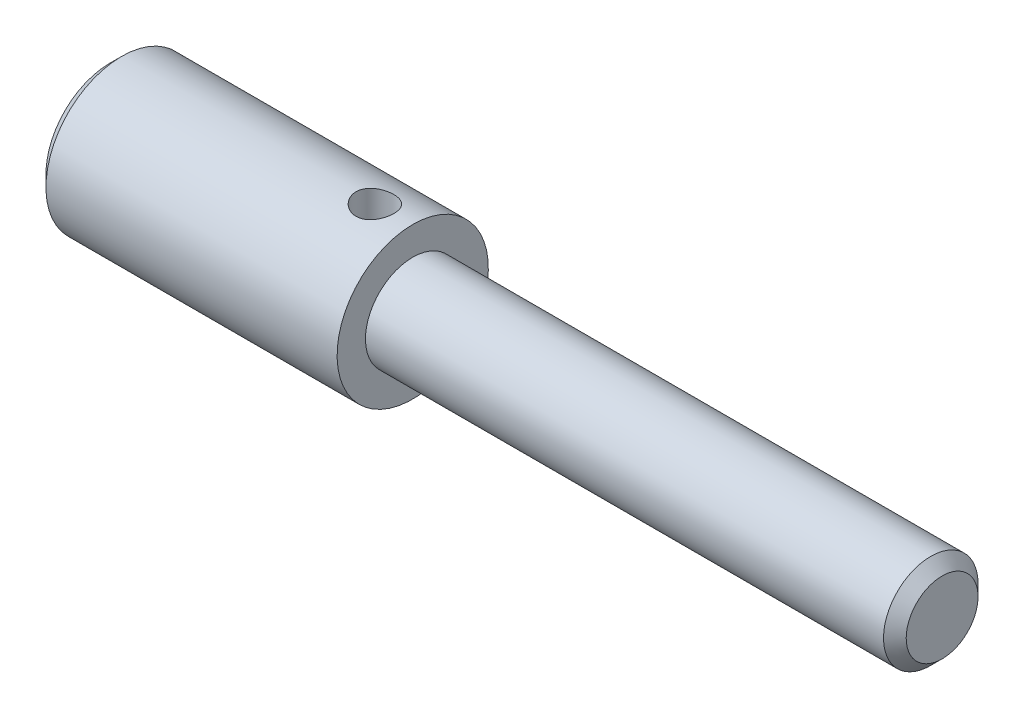
SolidWorks part; units mm, degrees
material "Латунь"
ref_plane "Спереди" through (0, 0, 0) normal (0, 0, 1) x (1, 0, 0)
ref_plane "Сверху" through (0, 0, 0) normal (0, 1, 0) x (1, 0, 0)
ref_plane "Справа" through (0, 0, 0) normal (1, 0, 0) x (0, 0, -1)
sketch "Эскиз1" plane through (0, 0, 0) normal (0, 0, 1) x (1, 0, 0)
  line L0 (0, 0) -> (16, 0)
  line L1 (16, 0) -> (16, -1.5)
  line L2 (16, -1.5) -> (44, -1.5)
  line L3 (44, -1.5) -> (44, -4)
  line L4 (44, -4) -> (0, -4)
  line L5 (0, -4) -> (0, 0)
  dimension "D1" = 4
  dimension "D2" = 2.5
  dimension "D3" = 44
  dimension "D4" = 16
revolve "Повернуть1" add sketch "Эскиз1" angle 360 about L4
cosmetic thread "Условное изображение резьбы1" parameters "D2"=6.891
cosmetic thread "Условное изображение резьбы2" parameters "D2"=4.11
chamfer "Фаска1" distance 0.6 angle 45 2 edges at (44, -1.5, 0) (0, 0, 0)
sketch "Эскиз2" plane through (0, 0, 0) normal (0, 1, 0) x (1, 0, 0)
  line L0 (0, 0) -> (14, 0) construction
  circle A0 centre (14, 0) radius 1
  dimension "D2" = 2
  dimension "D1" = 14
extrude "Вырез-Вытянуть1" cut sketch "Эскиз2" against normal up to next
